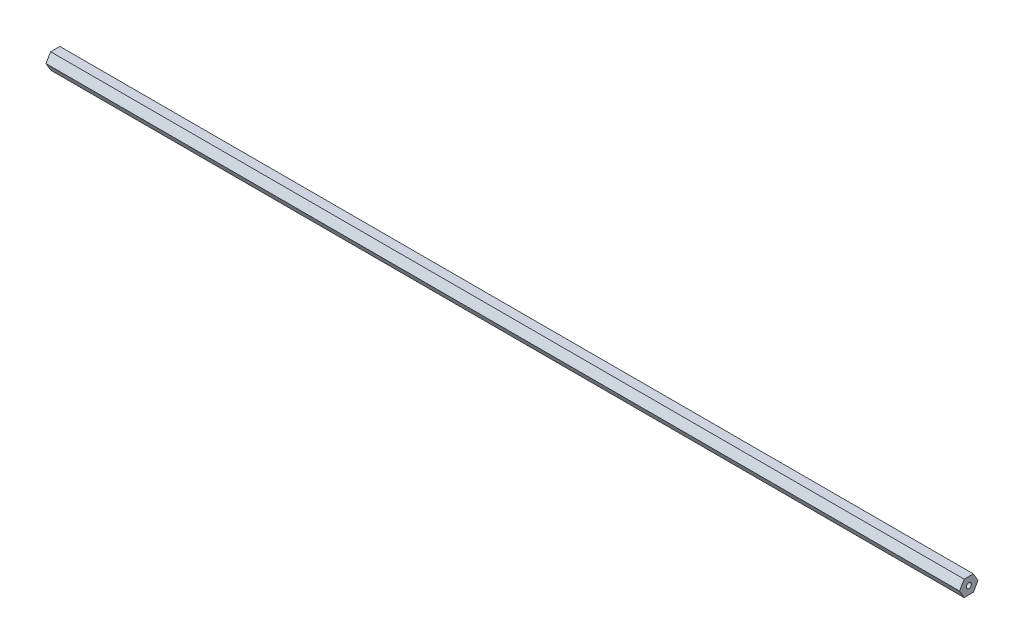
SolidWorks part; units mm, degrees
material "6061 Alloy"
ref_plane "Front Plane" through (0, 0, 0) normal (0, 0, 1) x (1, 0, 0)
ref_plane "Top Plane" through (0, 0, 0) normal (0, 1, 0) x (1, 0, 0)
ref_plane "Right Plane" through (0, 0, 0) normal (1, 0, 0) x (0, 0, -1)
sketch "Sketch1" plane through (0, 0, 0) normal (1, 0, 0) x (0, 0, -1)
  line L1 (7.3323, 0) -> (3.6662, 6.35)
  line L2 (3.6662, 6.35) -> (-3.6662, 6.35)
  line L3 (-3.6662, 6.35) -> (-7.3323, 0)
  line L4 (-7.3323, 0) -> (-3.6662, -6.35)
  line L5 (-3.6662, -6.35) -> (3.6662, -6.35)
  line L6 (3.6662, -6.35) -> (7.3323, 0)
  circle A0 centre (0, 0) radius 6.35 construction
  circle A1 centre (0, 0) radius 2.0193
  dimension "D1" = 12.7
  dimension "D2" = 4.0386
extrude "Boss-Extrude1" add sketch "Sketch1" along normal mid plane 727.075
sketch "Sketch2" plane through (363.5375, 0, 0) normal (1, 0, 0) x (0, 0, -1)
  circle A0 centre (0, 0) radius 5.125
  circle A1 centre (0, 0) radius 8.4922
  dimension "D1" = 10.25
extrude "Cut-Extrude1" [suppressed] cut sketch "Sketch2" against normal blind 7.112
mirror "Mirror1" [suppressed] about plane through (0, 0, 0) normal (1, 0, 0)
